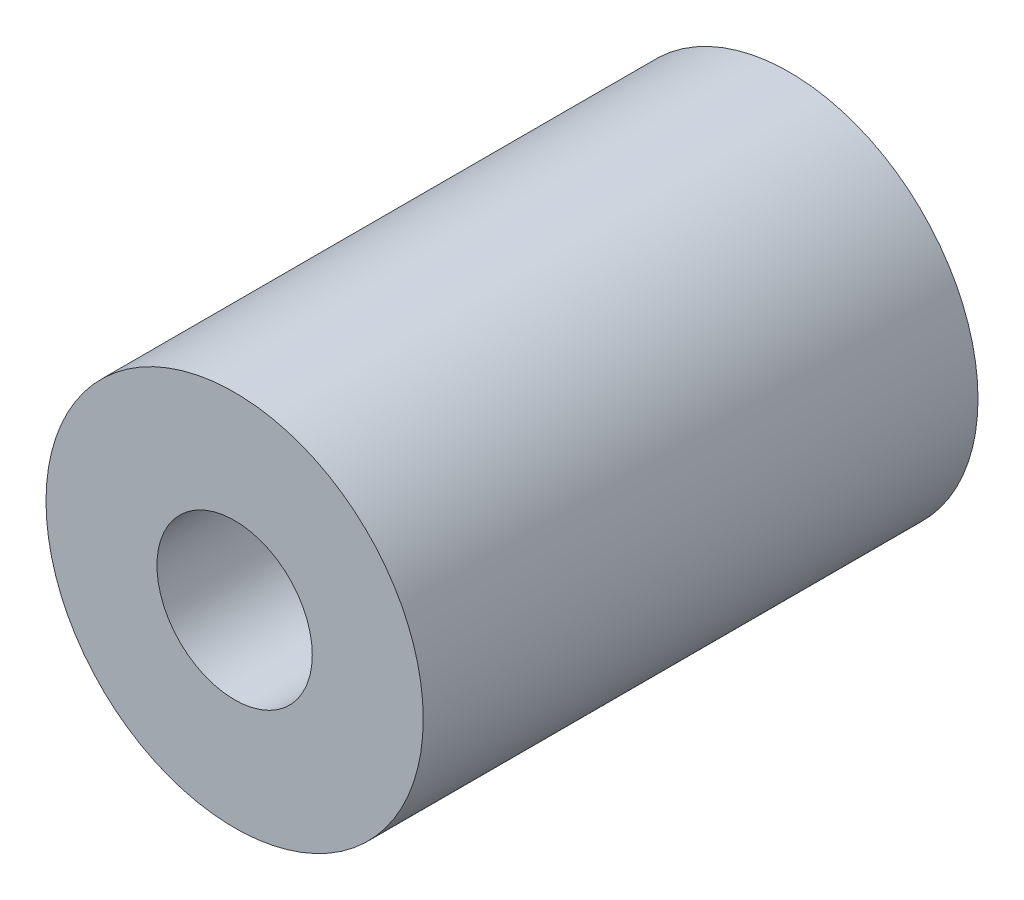
SolidWorks part; units mm, degrees
ref_plane "Front Plane" through (0, 0, 0) normal (0, 0, 1) x (1, 0, 0)
ref_plane "Top Plane" through (0, 0, 0) normal (0, 1, 0) x (1, 0, 0)
ref_plane "Right Plane" through (0, 0, 0) normal (1, 0, 0) x (0, 0, -1)
sketch "Sketch1" plane through (0, 0, 0) normal (0, 0, 1) x (1, 0, 0)
  circle A0 centre (0, 0) radius 3.4
  circle A1 centre (0, 0) radius 1.4
  dimension "D1" = 6.8
  dimension "3" = 2.8
extrude "Extrude1" add sketch "Sketch1" along normal mid plane 10
sketch3d "3D草图1"
  line L0 (0, 0, 0) -> (60.5499, 0, 0)
  line L1 (0, 0, 0) -> (0, 20.6679, 0)
  line L2 (0, 0, 0) -> (0, 0, 5)
  line L3 (0, 0, 5) -> (0, 0, -5) construction
  line L4 (0, 0, 5) -> (0, 0, -5) construction
